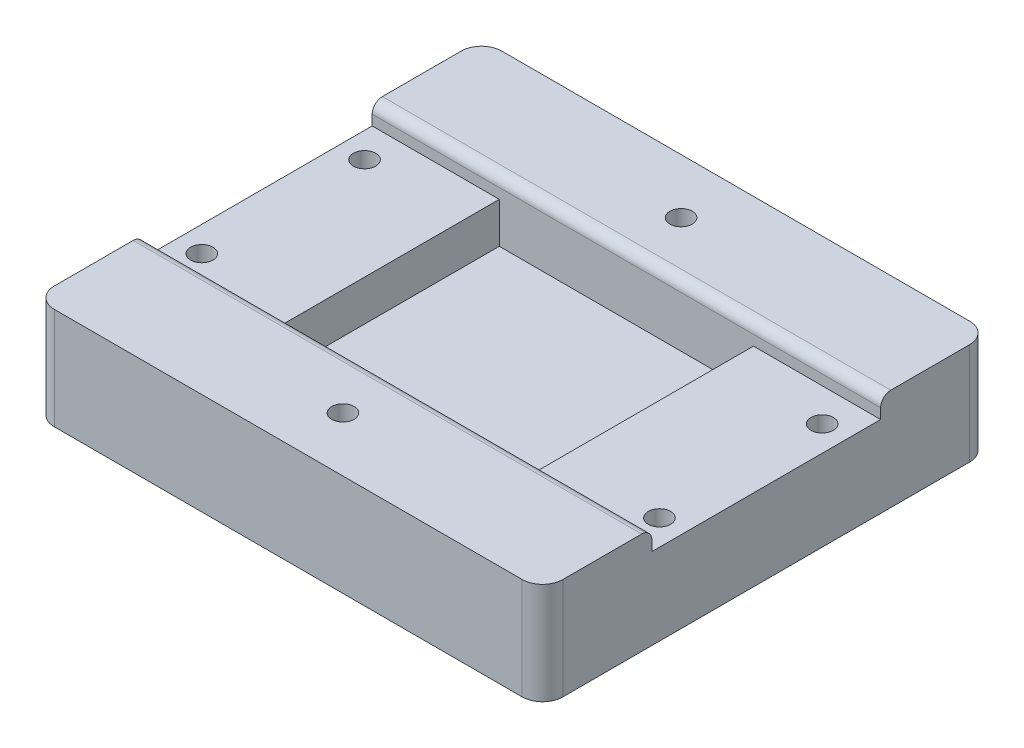
SolidWorks part; units mm, degrees
ref_plane "Alzado" through (0, 0, 0) normal (0, 0, 1) x (1, 0, 0)
ref_plane "Planta" through (0, 0, 0) normal (0, 1, 0) x (1, 0, 0)
ref_plane "Vista lateral" through (0, 0, 0) normal (1, 0, 0) x (0, 0, -1)
sketch "Croquis1" plane through (0, 0, 0) normal (0, 1, 0) x (1, 0, 0)
  line L1 (25, -22) -> (-25, -22)
  line L2 (25, -22) -> (25, 22)
  line L3 (25, 22) -> (-25, 22)
  line L4 (-25, -22) -> (-25, 22)
  line L5 (25, -22) -> (-25, 22) construction
  line L6 (25, 22) -> (-25, -22) construction
  point P0 (0, 0)
  dimension "D1" = 44
  dimension "D2" = 50
extrude "Saliente-Extruir1" add sketch "Croquis1" along normal blind 10
sketch "Croquis2" plane through (0, 10, 0) normal (0, 1, 0) x (1, 0, 0)
  line L1 (29, -11.25) -> (-29, -11.25)
  line L2 (29, -11.25) -> (29, 11.25)
  line L3 (29, 11.25) -> (-29, 11.25)
  line L4 (-29, -11.25) -> (-29, 11.25)
  line L5 (29, -11.25) -> (-29, 11.25) construction
  line L6 (29, 11.25) -> (-29, -11.25) construction
  point P0 (0, 0)
  dimension "D1" = 22.5
  dimension "D2" = 58
extrude "Cortar-Extruir2" cut sketch "Croquis2" against normal blind 2
sketch "Croquis3" plane through (0, 8, 0) normal (0, 1, 0) x (1, 0, 0)
  line L0 (25, 11.25) -> (-25, 11.25) construction
  line L1 (12.5, -11.25) -> (-12.5, -11.25)
  line L2 (12.5, -11.25) -> (12.5, 11.25)
  line L3 (12.5, 11.25) -> (-12.5, 11.25)
  line L4 (-12.5, -11.25) -> (-12.5, 11.25)
  line L5 (12.5, -11.25) -> (-12.5, 11.25) construction
  line L6 (12.5, 11.25) -> (-12.5, -11.25) construction
  point P0 (0, 0)
  dimension "D1" = 25
extrude "Cortar-Extruir3" cut sketch "Croquis3" against normal blind 4
sketch "Croquis4" plane through (0, 8, 0) normal (0, 1, 0) x (1, 0, 0)
  line L0 (-25, 8) -> (25, 8) construction
  line L1 (-25, 11.25) -> (-25, -11.25) construction
  line L2 (25, -11.25) -> (25, 11.25) construction
  line L3 (-25, -8) -> (25, -8) construction
  line L4 (-22.5, 11.25) -> (-22.5, -11.25) construction
  line L5 (-12.5, 11.25) -> (-25, 11.25) construction
  line L6 (-25, -11.25) -> (25, -11.25) construction
  line L7 (22.5, 11.25) -> (22.5, -11.25) construction
  line L8 (25, 11.25) -> (-25, 11.25) construction
  line L9 (-12.5, 11.25) -> (-12.5, -11.25) construction
  line L10 (12.5, -11.25) -> (12.5, 11.25) construction
  circle A0 centre (-22.5, 8) radius 1.1
  circle A1 centre (-22.5, -8) radius 1.1
  circle A2 centre (22.5, 8) radius 1.1
  circle A3 centre (22.5, -8) radius 1.1
  point P23 (-22.5, 8)
  point P24 (-22.5, -8)
  point P25 (22.5, -8)
  point P26 (22.5, 8)
  dimension "D5" = 2.2
  dimension "D6" = 2.2
  dimension "D7" = 2.2
  dimension "D8" = 2.2
  dimension "D1" = 8
  dimension "D2" = 8
  dimension "D3" = 10
  dimension "D4" = 10
extrude "Cortar-Extruir4" cut sketch "Croquis4" against normal blind 5
sketch "Croquis5" plane through (0, 10, 0) normal (0, 1, 0) x (1, 0, 0)
  line L0 (0, 22) -> (0, -22) construction
  line L1 (25, 22) -> (-25, 22) construction
  line L2 (-25, -22) -> (25, -22) construction
  line L3 (-25, 16.625) -> (25, 16.625) construction
  line L4 (-25, 22) -> (-25, 11.25) construction
  line L5 (25, 11.25) -> (25, 22) construction
  line L6 (-25, -16.625) -> (25, -16.625) construction
  line L7 (-25, -11.25) -> (-25, -22) construction
  line L8 (25, -22) -> (25, -11.25) construction
  circle A0 centre (0, 16.625) radius 1.1
  circle A1 centre (0, -16.625) radius 1.1
  point P18 (0, 16.625)
  point P19 (0, -16.625)
  dimension "D1" = 2.2
  dimension "D2" = 2.2
extrude "Cortar-Extruir5" cut sketch "Croquis5" against normal blind 5
fillet "Redondeo1" radius 2 4 edges at (-25, 5, -22) (-25, 5, 22) (25, 5, 22) (25, 5, -22)
fillet "Redondeo2" radius 1 2 edges at (0, 10, 11.25) (0, 10, -11.25)
